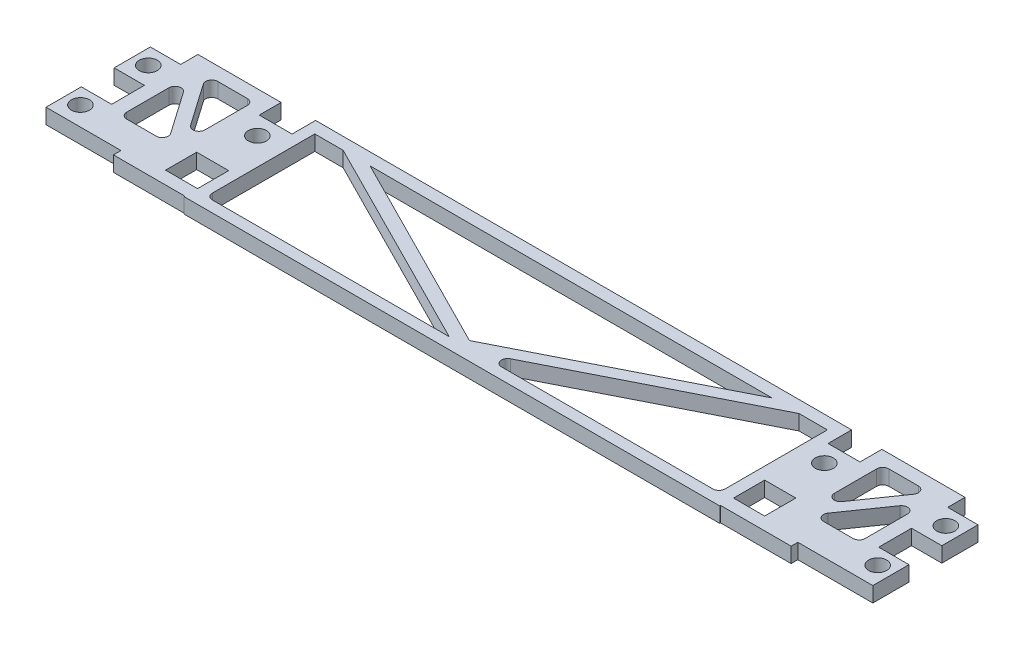
SolidWorks part; units mm, degrees
material "6061-T6 (SS)"
ref_plane "Front Plane" through (0, 0, 0) normal (0, 0, 1) x (1, 0, 0)
ref_plane "Top Plane" through (0, 0, 0) normal (0, 1, 0) x (1, 0, 0)
ref_plane "Right Plane" through (0, 0, 0) normal (1, 0, 0) x (0, 0, -1)
sketch "Sketch1" plane through (0, 0, 0) normal (0, 1, 0) x (1, 0, 0)
  line L0 (-9.4034, 9.2883) -> (-9.4034, 15.8161) construction
  line L1 (8.3766, 27.5636) -> (-9.4034, 27.5636) construction
  line L2 (-9.4034, 9.2883) -> (-15.7534, 9.2883) construction
  line L3 (8.3766, 2.8113) -> (8.3766, 9.3391)
  line L4 (-15.7534, 1.3508) -> (-0.2159, 1.3508) construction
  line L5 (-15.7534, 9.2883) -> (-15.7534, 1.3508) construction
  line L6 (-9.4034, 23.7536) -> (-9.4034, 27.5636) construction
  line L7 (8.3766, 2.8113) -> (15.0822, 2.8113)
  line L8 (8.3766, 9.3391) -> (15.0822, 9.3391)
  line L9 (8.3766, 22.8011) -> (14.9044, 22.8011) construction
  line L10 (-9.4034, 15.8161) -> (-15.7534, 15.8161) construction
  line L11 (8.3766, 22.8011) -> (8.3766, 27.5636) construction
  line L12 (14.9044, 2.8113) -> (14.9044, -0.2367) construction
  line L13 (-9.4034, 23.7536) -> (-15.7534, 23.7536) construction
  line L14 (-15.7534, 15.8161) -> (-15.7534, 23.7536) construction
  line L15 (-0.2159, 1.3508) -> (-0.2159, -0.2367) construction
  line L16 (14.9044, 9.3391) -> (14.9044, 22.8011) construction
  line L17 (-0.2159, -0.2367) -> (14.9044, -0.2367) construction
  line L18 (8.3766, 27.5636) -> (8.3766, 22.8011) construction
  line L19 (8.3766, 22.8011) -> (14.9044, 22.8011) construction
  line L20 (-6.2284, 24.3886) -> (5.2016, 8.0019) construction
  line L21 (-0.0381, -0.0589) -> (15.0822, -0.0589) construction
  line L22 (-0.0381, 1.5286) -> (-0.0381, -0.0589) construction
  line L23 (-15.5756, 1.5286) -> (-0.0381, 1.5286) construction
  line L24 (-15.5756, 9.1105) -> (-15.5756, 1.7064)
  line L25 (-9.2256, 9.1105) -> (-15.5756, 9.1105)
  line L26 (-9.2256, 9.1105) -> (-9.2256, 15.9939)
  line L27 (71.1654, 31.9922) -> (71.1654, -0.2367) construction
  line L28 (14.9044, -0.2367) -> (127.4264, -0.2367) construction
  line L29 (14.9044, -0.2367) -> (14.9044, 31.9922) construction
  line L30 (14.9044, 31.9922) -> (127.4264, 31.9922) construction
  line L31 (127.4264, -0.2367) -> (127.4264, 31.9922)
  line L32 (127.4264, -0.2367) -> (127.4264, 31.9922)
  line L33 (127.4264, 9.3391) -> (127.4264, 22.8011) construction
  line L34 (148.5592, 24.3886) -> (137.1292, 8.0019) construction
  line L35 (133.9542, 22.8011) -> (127.4264, 22.8011) construction
  line L36 (133.9542, 27.5636) -> (133.9542, 22.8011) construction
  line L37 (142.5467, -0.2367) -> (127.4264, -0.2367) construction
  line L38 (142.5467, 1.3508) -> (142.5467, -0.2367) construction
  line L39 (147.5175, 25.1152) -> (136.0875, 8.7284)
  line L40 (149.6008, 23.6621) -> (138.1708, 7.2753)
  line L41 (158.0842, 15.8161) -> (158.0842, 23.7536) construction
  line L42 (151.7342, 23.7536) -> (158.0842, 23.7536) construction
  line L43 (133.9542, 22.8011) -> (133.9542, 27.5636) construction
  line L44 (151.7342, 15.8161) -> (158.0842, 15.8161) construction
  line L45 (133.9542, 22.8011) -> (127.4264, 22.8011) construction
  line L46 (137.1292, 24.3886) -> (137.1292, 8.0019)
  line L47 (133.9542, 9.3391) -> (127.4264, 9.3391)
  line L48 (133.9542, 2.8113) -> (127.4264, 2.8113)
  line L49 (151.7342, 23.7536) -> (151.7342, 27.5636) construction
  line L50 (148.5592, 8.0019) -> (137.1292, 8.0019)
  line L51 (158.0842, 9.2883) -> (158.0842, 1.3508) construction
  line L52 (158.0842, 1.3508) -> (142.5467, 1.3508) construction
  line L53 (133.9542, 2.8113) -> (133.9542, 9.3391)
  line L54 (151.7342, 9.2883) -> (158.0842, 9.2883) construction
  line L55 (148.5592, 24.3886) -> (148.5592, 8.0019)
  line L56 (133.9542, 27.5636) -> (151.7342, 27.5636) construction
  line L57 (148.5592, 24.3886) -> (137.1292, 24.3886)
  line L58 (151.7342, 9.2883) -> (151.7342, 15.8161) construction
  line L60 (124.8864, 2.3033) -> (124.8864, 29.4522)
  line L61 (17.4444, 2.3033) -> (124.8864, 2.3033)
  line L62 (17.4444, 2.3033) -> (17.4444, 29.4522)
  line L63 (21.1813, 27.5636) -> (71.1654, 2.3033)
  line L64 (71.1654, 2.3033) -> (121.1494, 27.5636)
  line L65 (16.8716, 28.3187) -> (17.4444, 28.0292)
  line L66 (71.1654, 0.8804) -> (123.9651, 27.5636)
  line L67 (18.0172, 30.5857) -> (20.2601, 29.4522)
  line L68 (71.1654, 3.7263) -> (118.3337, 27.5636)
  line L69 (-9.2256, 15.9939) -> (-15.5756, 15.9939)
  line L70 (-15.5756, 15.9939) -> (-15.5756, 23.5758)
  line L71 (-9.2256, 23.5758) -> (-15.5756, 23.5758)
  line L72 (-9.2256, 23.5758) -> (-9.2256, 27.3858)
  line L73 (8.1988, 27.3858) -> (-9.2256, 27.3858) construction
  line L74 (8.1988, 22.6233) -> (8.1988, 27.3858) construction
  line L75 (8.1988, 22.6233) -> (15.0822, 22.6233) construction
  line L76 (8.1988, 9.5169) -> (15.0822, 9.5169) construction
  line L77 (8.1988, 2.6335) -> (8.1988, 9.5169) construction
  line L78 (8.1988, 2.6335) -> (15.0822, 2.6335) construction
  line L79 (8.1988, 27.5636) -> (8.1988, 22.6233)
  line L80 (8.1988, 22.6233) -> (15.0822, 22.6233)
  line L81 (-6.2284, 24.3886) -> (5.2016, 24.3886)
  line L82 (-6.2284, 24.3886) -> (-6.2284, 8.0019)
  line L83 (-6.2284, 8.0019) -> (5.2016, 8.0019)
  line L84 (5.2016, 24.3886) -> (5.2016, 8.0019)
  line L85 (-7.2701, 23.6621) -> (4.1599, 7.2753)
  line L86 (15.0822, -0.0589) -> (127.4264, -0.0589)
  line L87 (15.0822, -0.0589) -> (15.0822, 31.8144)
  line L88 (15.0822, 31.8144) -> (127.4264, 31.8144)
  line L89 (-5.1868, 25.1152) -> (6.2432, 8.7284)
  line L90 (134.132, 9.5169) -> (127.6042, 9.5169) construction
  line L91 (133.9542, 22.6233) -> (127.4264, 22.6233) construction
  line L92 (15.0822, -0.0589) -> (14.9044, -0.0589)
  line L93 (134.3098, 22.6233) -> (127.4264, 22.6233)
  line L94 (134.132, 27.5636) -> (134.132, 22.5011)
  line L95 (134.132, 2.6335) -> (127.4264, 2.6335) construction
  line L96 (134.132, 2.6335) -> (134.132, 9.5169) construction
  line L97 (134.132, 9.5169) -> (127.4264, 9.5169) construction
  line L98 (127.6042, 9.5169) -> (127.6042, 22.6233) construction
  line L99 (134.132, 22.6233) -> (127.6042, 22.6233) construction
  line L100 (134.132, 22.6233) -> (134.132, 27.3858) construction
  line L101 (134.132, 27.3858) -> (151.5564, 27.3858) construction
  line L102 (151.5564, 23.5758) -> (151.5564, 27.3858)
  line L103 (151.5564, 23.5758) -> (157.9064, 23.5758)
  line L104 (157.9064, 15.9939) -> (157.9064, 23.5758)
  line L105 (151.5564, 15.9939) -> (157.9064, 15.9939)
  line L106 (151.5564, 9.1105) -> (151.5564, 15.9939)
  line L107 (151.5564, 9.1105) -> (157.9064, 9.1105)
  line L108 (157.9064, 9.1105) -> (157.9064, 1.5286)
  line L109 (157.9064, 1.5286) -> (142.1911, 1.5286)
  line L110 (142.3689, 1.5286) -> (142.3689, -0.0589) construction
  line L111 (142.3689, -0.0589) -> (127.4264, -0.0589) construction
  line L112 (134.3098, 27.208) -> (151.3786, 27.208) construction
  line L113 (8.1988, 27.208) -> (-9.2256, 27.208)
  line L114 (8.021, 27.208) -> (-9.0478, 27.208) construction
  line L115 (-9.2256, 23.5758) -> (-15.5756, 23.5758) construction
  line L116 (-9.0478, 23.398) -> (-9.0478, 27.208) construction
  line L117 (-15.3978, 1.7064) -> (0.1397, 1.7064) construction
  line L118 (-15.5756, 9.1105) -> (-15.5756, 1.5286) construction
  line L119 (151.3786, 16.1717) -> (157.7286, 16.1717) construction
  line L120 (151.5564, 15.9939) -> (157.9064, 15.9939) construction
  line L121 (-15.5756, 1.7064) -> (0.1397, 1.7064)
  line L122 (0.1397, 1.7064) -> (0.1397, 0.1189)
  line L123 (0.1397, 0.1189) -> (15.0822, 0.1189)
  line L124 (157.9064, 1.5286) -> (142.3689, 1.5286) construction
  line L125 (142.1911, 1.7064) -> (142.1911, 0.1189) construction
  line L126 (134.132, 27.5636) -> (134.132, 22.8011) construction
  line L127 (142.1911, 0.1189) -> (127.4264, 0.1189)
  line L128 (142.1911, 1.5286) -> (142.1911, 0.1189)
  line L129 (15.0822, 27.5636) -> (127.4264, 27.5636)
  line L130 (15.0822, 25.0236) -> (127.4264, 25.0236)
  line L131 (23.997, 27.5636) -> (71.1654, 3.7263)
  line L132 (18.0172, 30.5857) -> (71.1654, 3.7263) construction
  line L133 (122.0707, 29.4522) -> (124.3136, 30.5857)
  line L134 (71.1654, 3.7263) -> (124.3136, 30.5857) construction
  line L135 (71.1654, 2.3033) -> (124.8864, 29.4522) construction
  line L136 (124.8864, 28.0292) -> (125.4592, 28.3187)
  line L137 (134.132, 27.208) -> (151.5564, 27.208)
  line L138 (71.1654, 0.8804) -> (125.4592, 28.3187) construction
  line L139 (17.4444, 29.4522) -> (71.1654, 2.3033) construction
  line L140 (134.3098, 22.4455) -> (127.782, 22.4455) construction
  line L141 (18.3656, 27.5636) -> (71.1654, 0.8804)
  line L142 (16.8716, 28.3187) -> (71.1654, 0.8804) construction
  line L144 (127.782, 9.5169) -> (127.782, 22.4455) construction
  line L148 (-9.0478, 23.398) -> (-15.3978, 23.398) construction
  line L149 (-15.3978, 16.1717) -> (-15.3978, 23.398) construction
  line L150 (-9.0478, 16.1717) -> (-15.3978, 16.1717) construction
  line L151 (-9.0478, 8.9327) -> (-9.0478, 16.1717) construction
  line L152 (-9.0478, 8.9327) -> (-15.3978, 8.9327) construction
  line L153 (-15.3978, 8.9327) -> (-15.3978, 1.7064) construction
  line L154 (8.021, 22.4455) -> (8.021, 27.208) construction
  line L155 (8.021, 22.4455) -> (15.0822, 22.4455) construction
  line L159 (134.3098, 22.4455) -> (134.3098, 27.208) construction
  line L160 (151.3786, 23.398) -> (157.7286, 23.398) construction
  line L161 (151.3786, 23.398) -> (151.3786, 27.208) construction
  line L162 (157.7286, 16.1717) -> (157.7286, 23.398) construction
  line L163 (151.3786, 8.9327) -> (151.3786, 16.1717) construction
  line L164 (151.3786, 8.9327) -> (157.7286, 8.9327) construction
  line L165 (157.7286, 8.9327) -> (157.7286, 1.7064) construction
  line L166 (157.7286, 1.7064) -> (142.1911, 1.7064) construction
  line L167 (17.4444, 29.4522) -> (124.8864, 29.4522) construction
  dimension "D3" = 0.1778
  dimension "D4" = 2.54
  dimension "D16" = 112.522
  dimension "D17" = 2.54
  dimension "D18" = 1.27
  dimension "D19" = 1.27
  dimension "D22" = 0.1778
  dimension "D23" = 0.1778
  dimension "D24" = 0.1778
extrude "Boss-Extrude1" add sketch "Sketch1" along normal blind 3.175
ref_plane "Plane1" through (71.2833, 2.1981, -0.2526) normal (-0.9995, -0.0308, 0.0035) x (0.0035, 0.0001, 1)
hole_wizard "#6 Clearance Hole1" positions "Sketch3" profile "Sketch2" hole size "#6" standard "ANSI Inch"
sketch "Sketch3" plane through (0.0241, 3.175, -12.5095) normal (0, -1, 0) x (-1, 0, 0)
  point P38 (-130.5773, 6.1641)
  point P40 (-154.7073, 7.4997)
  point P42 (-154.7073, -6.7878)
  point P44 (-154.7073, 7.4997)
  point P48 (-11.737, 6.1641)
  point P54 (12.393, -6.7878)
  point P57 (12.4628, 7.4997)
sketch "Sketch2" plane through (130.6014, 3.175, -18.6736) normal (1, 0, 0) x (0, 0, 1)
  line L0 (0, 0) -> (0, 7.4908)
  line L1 (0, 7.4908) -> (1.8986, 6.35)
  line L2 (1.8986, 6.35) -> (1.8986, 0)
  line L5 (1.8986, 0) -> (0, 0)
  line L10 (0, 7.4908) -> (-1.8987, 6.35) construction
  line L11 (0, -6.35) -> (0, 107.95) construction
  dimension "Hole Dia." = 3.7973
  dimension "Hole Depth" = 6.35
  dimension "Drill Angle" = 118
fillet "Fillet1" radius 1.27 15 edges at (148.5592, 1.5875, -8.0019) (138.6776, 1.5875, -8.0019) (137.1292, 1.5875, -10.2218) (148.5592, 1.5875, -22.1687) (147.0108, 1.5875, -24.3886) (137.1292, 1.5875, -24.3886) (124.8864, 1.5875, -2.3033) (73.9811, 1.5875, -2.3033) (17.4444, 1.5875, -2.3033) (-6.2284, 1.5875, -22.1687) (-6.2284, 1.5875, -8.0019) (3.6532, 1.5875, -8.0019) (5.2016, 1.5875, -10.2218) (5.2016, 1.5875, -24.3886) (-4.68, 1.5875, -24.3886)
